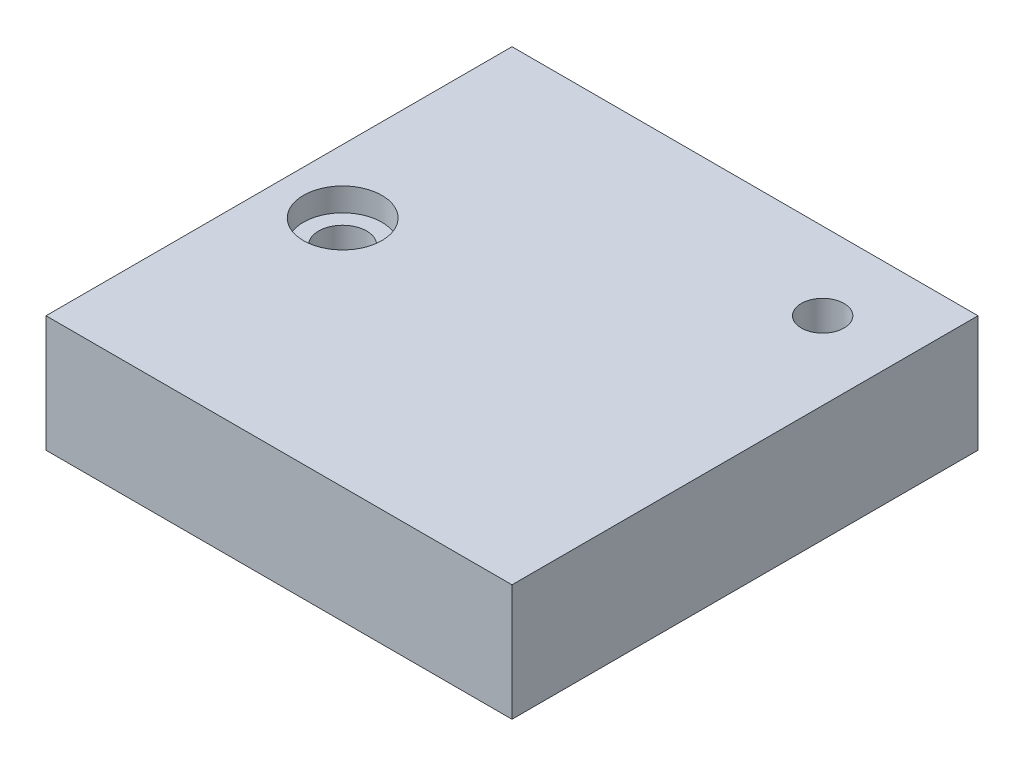
SolidWorks part; units mm, degrees
ref_plane "Front Plane" through (0, 0, 0) normal (0, 0, 1) x (1, 0, 0)
ref_plane "Top Plane" through (0, 0, 0) normal (0, 1, 0) x (1, 0, 0)
ref_plane "Right Plane" through (0, 0, 0) normal (1, 0, 0) x (0, 0, -1)
sketch "Sketch2" plane through (0, 0, 0) normal (0, 1, 0) x (1, 0, 0)
  line L1 (-30, 30) -> (30, 30)
  line L2 (-30, 30) -> (-30, -30)
  line L3 (-30, -30) -> (30, -30)
  line L4 (30, 30) -> (30, -30)
  line L5 (-30, 30) -> (30, -30) construction
  line L6 (-30, -30) -> (30, 30) construction
  point P0 (0, 0)
  dimension "D1" = 60
  dimension "D2" = 60
extrude "Boss-Extrude1" add sketch "Sketch2" along normal blind 15 contours L2 L1 L4 L3
sketch "Sketch3" plane through (0, 15, 0) normal (0, 1, 0) x (1, 0, 0)
  circle A0 centre (-21.8045, 0) radius 5.05
  dimension "D1" = 10.1
extrude "Cut-Extrude3" cut sketch "Sketch3" against normal blind 3
sketch "Sketch5" plane through (0, 0, 0) normal (0, 1, 0) x (1, 0, 0)
  circle A0 centre (-21.8045, 0) radius 3.1
  circle A1 centre (-21.8045, 0) radius 5.05 construction
  dimension "D1" = 6.2
extrude "Cut-Extrude4" cut sketch "Sketch5" along normal blind 12
sketch "Sketch6" plane through (0, 15, 0) normal (0, 1, 0) x (1, 0, 0)
  line L0 (-30, 30) -> (30, 30) construction
  line L1 (30, 30) -> (30, -30) construction
  circle A0 centre (20, 20) radius 2.75
  dimension "D1" = 5.5
  dimension "D2" = 10
  dimension "D3" = 10
extrude "Cut-Extrude5" cut sketch "Sketch6" against normal blind 5.5
